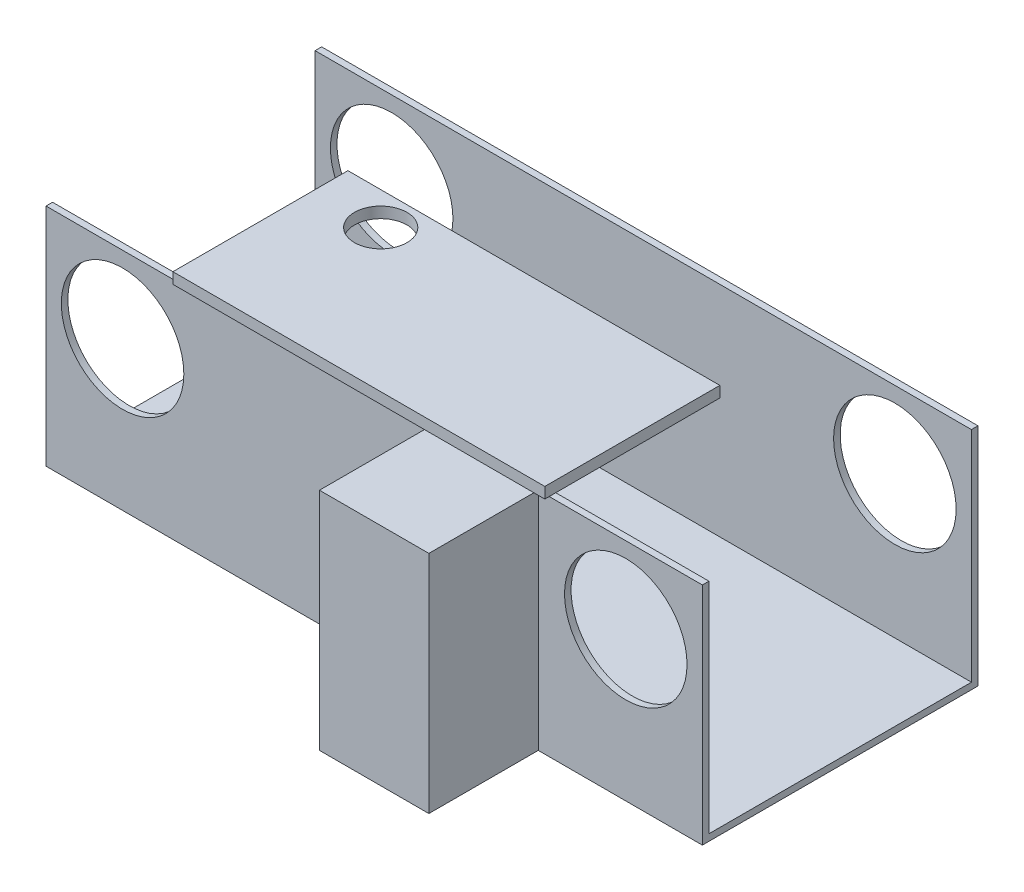
SolidWorks part; units mm, degrees
ref_plane "Front Plane" through (0, 0, 0) normal (0, 0, 1) x (1, 0, 0)
ref_plane "Top Plane" through (0, 0, 0) normal (0, 1, 0) x (1, 0, 0)
ref_plane "Right Plane" through (0, 0, 0) normal (1, 0, 0) x (0, 0, -1)
sketch "Sketch1" plane through (0, 0, 0) normal (0, 1, 0) x (1, 0, 0)
  line L1 (-146.0641, 51.656) -> (153.9359, 51.656)
  line L2 (-146.0641, 51.656) -> (-146.0641, -74.344)
  line L3 (-146.0641, -74.344) -> (153.9359, -74.344)
  line L4 (153.9359, 51.656) -> (153.9359, -74.344)
  dimension "D1" = 300
  dimension "D2" = 126
extrude "Boss-Extrude2" add sketch "Sketch1" along normal blind 3
sketch "Sketch3" plane through (0, 3, 0) normal (0, 1, 0) x (1, 0, 0)
  line L0 (-146.0641, 51.656) -> (-146.0641, -74.344) construction
  line L1 (-146.0641, -71.344) -> (153.9359, -71.344)
  line L2 (-146.0641, -71.344) -> (-146.0641, -74.344)
  line L3 (-146.0641, -74.344) -> (153.9359, -74.344)
  line L4 (153.9359, -71.344) -> (153.9359, -74.344)
  line L5 (153.9359, -74.344) -> (153.9359, 51.656) construction
  line L6 (-146.0641, 51.656) -> (153.9359, 51.656)
  line L7 (-146.0641, 51.656) -> (-146.0641, 48.656)
  line L8 (-146.0641, 48.656) -> (153.9359, 48.656)
  line L9 (153.9359, 51.656) -> (153.9359, 48.656)
  dimension "D1" = 3
  dimension "D2" = 3
extrude "Boss-Extrude3" add sketch "Sketch3" along normal blind 100
sketch "Sketch4" plane through (0, 0, 74.344) normal (0, 0, 1) x (1, 0, 0)
  line L0 (-146.0641, 103) -> (-146.0641, 0) construction
  line L1 (-146.0641, 103) -> (153.9359, 103) construction
  line L2 (3.9359, 103) -> (3.9359, 0) construction
  line L3 (-146.0641, 0) -> (153.9359, 0) construction
  circle A0 centre (-111.0641, 68) radius 28
  circle A1 centre (118.9359, 68) radius 28
  dimension "D1" = 35
  dimension "D2" = 35
extrude "Cut-Extrude1" cut sketch "Sketch4" against normal blind 186
sketch "Sketch5" plane through (0, 0, 74.344) normal (0, 0, 1) x (1, 0, 0)
  line L1 (-146.0641, 103) -> (153.9359, 103) construction
  line L2 (-146.0641, 0) -> (153.9359, 0) construction
  line L3 (53.9359, 103) -> (53.9359, 0) construction
  line L4 (78.9359, 0) -> (28.9359, 0)
  line L5 (78.9359, 0) -> (78.9359, 103)
  line L6 (78.9359, 103) -> (28.9359, 103)
  line L7 (28.9359, 0) -> (28.9359, 103)
  line L8 (78.9359, 0) -> (28.9359, 103) construction
  line L9 (78.9359, 103) -> (28.9359, 0) construction
  point P0 (53.9359, 51.5)
  dimension "D1" = 100
  dimension "D2" = 25
extrude "Boss-Extrude9" add sketch "Sketch5" along normal blind 50
sketch "Sketch9" plane through (0, 103, 0) normal (0, 1, 0) x (1, 0, 0)
  line L0 (-946.0641, -76.344) -> (49053.9359, -76.344) construction
  line L5 (-146.0641, -11.344) -> (153.9359, -11.344) construction
  line L6 (-146.0641, 48.656) -> (-146.0641, -71.344) construction
  line L7 (153.9359, -71.344) -> (153.9359, 48.656) construction
  line L8 (-146.0641, 3.656) -> (153.9359, 3.656) construction
  line L9 (53.9359, -124.344) -> (53.9359, 3.656) construction
  line L10 (78.9359, -124.344) -> (28.9359, -124.344) construction
  line L11 (83.9359, 3.656) -> (83.9359, -76.344) construction
  line L12 (-86.0641, 3.656) -> (-86.0641, -76.344) construction
  line L13 (-56.0641, 3.656) -> (-56.0641, -76.344) construction
  line L14 (-86.0641, 3.656) -> (83.9359, 3.656)
  line L15 (-86.0641, 3.656) -> (-86.0641, -76.344)
  line L16 (-86.0641, -76.344) -> (83.9359, -76.344)
  line L17 (83.9359, 3.656) -> (83.9359, -76.344)
  circle A0 centre (-56.0641, -11.344) radius 12
  dimension "D1" = 15
  dimension "D2" = 80
  dimension "D3" = 30
  dimension "D4" = 140
  dimension "D5" = 30
extrude "Boss-Extrude14" add sketch "Sketch9" along normal blind 5
